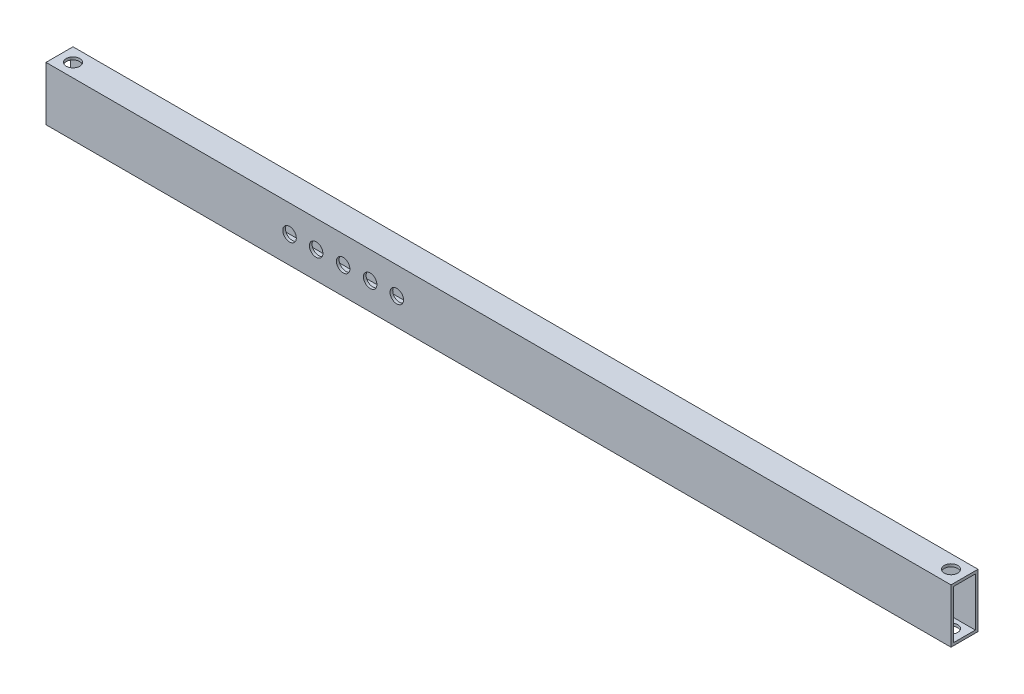
SolidWorks part; units mm, degrees
ref_plane "Front Plane" through (0, 0, 0) normal (0, 0, 1) x (1, 0, 0)
ref_plane "Top Plane" through (0, 0, 0) normal (0, 1, 0) x (1, 0, 0)
ref_plane "Right Plane" through (0, 0, 0) normal (1, 0, 0) x (0, 0, -1)
sketch "Sketch1" plane through (0, 0, 0) normal (1, 0, 0) x (0, 0, -1)
  line L0 (-4, -9) -> (-4, 9)
  line L1 (-5, -10) -> (5, -10)
  line L2 (-5, -10) -> (-5, 10)
  line L3 (-5, 10) -> (5, 10)
  line L4 (5, -10) -> (5, 10)
  line L5 (-5, -10) -> (5, 10) construction
  line L6 (-5, 10) -> (5, -10) construction
  line L7 (-4, 9) -> (4, 9)
  line L8 (4, -9) -> (4, 9)
  line L9 (-4, -9) -> (4, -9)
  point P0 (0, 0)
  dimension "D1" = 20
  dimension "D2" = 10
  dimension "D3" = 1
extrude "Boss-Extrude1" add sketch "Sketch1" along normal blind 225 and the other way blind 110
sketch "Sketch2" plane through (0, 0, 5) normal (0, 0, 1) x (1, 0, 0)
  line L0 (0, -10) -> (0, 10) construction
  line L1 (-110, -10) -> (225, -10) construction
  line L2 (-110, 10) -> (225, 10) construction
  circle A0 centre (-19.85, 0) radius 2.5
  circle A1 centre (-10, 0) radius 2.5
  circle A2 centre (0, 0) radius 2.5
  circle A3 centre (19.85, 0) radius 2.5
  circle A4 centre (10, 0) radius 2.5
  dimension "D5" = 5
  dimension "D6" = 5
  dimension "D7" = 5
  dimension "D1" = 10
  dimension "D3" = 9.85
  dimension "D4" = 10
  dimension "D8" = 9.85
  dimension "D9" = 10
extrude "Cut-Extrude1" cut sketch "Sketch2" against normal blind 1
sketch "Sketch3" plane through (0, 10, 0) normal (0, 1, 0) x (1, 0, 0)
  line L0 (225, 5) -> (225, -5) construction
  line L1 (-110, 5) -> (225, 5) construction
  line L2 (-110, -5) -> (225, -5) construction
  line L3 (-110, 5) -> (-110, -5) construction
  circle A0 centre (220, 0) radius 2.5
  circle A1 centre (-105, 0) radius 2.5
  point P4 (225, 0)
  dimension "D3" = 5
  dimension "D4" = 5
  dimension "D1" = 5
  dimension "D2" = 5
  dimension "D5" = 5
  dimension "D6" = 5
extrude "Cut-Extrude2" cut sketch "Sketch3" against normal blind 20
